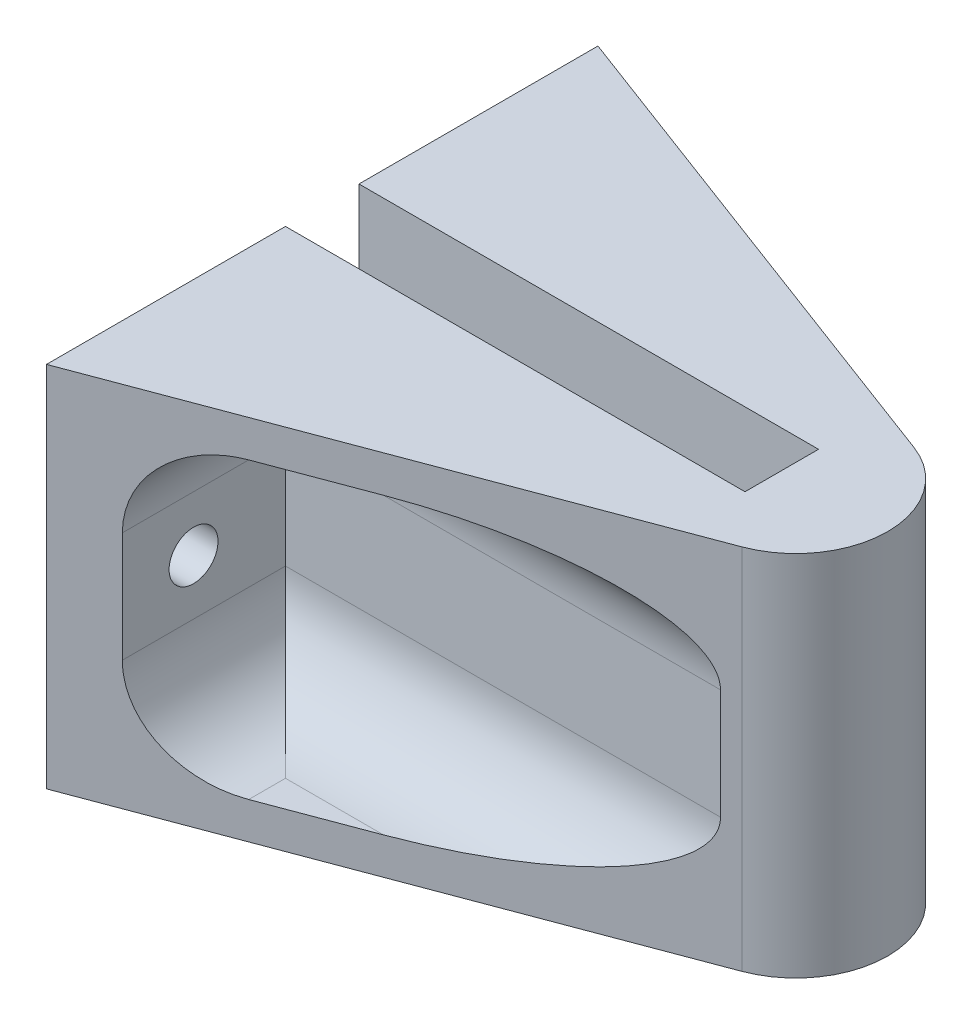
SolidWorks part; units mm, degrees
ref_plane "Спереди" through (0, 0, 0) normal (0, 0, 1) x (1, 0, 0)
ref_plane "Сверху" through (0, 0, 0) normal (0, 1, 0) x (1, 0, 0)
ref_plane "Справа" through (0, 0, 0) normal (1, 0, 0) x (0, 0, -1)
sketch "Эскиз1" plane through (0, 0, 0) normal (0, 1, 0) x (1, 0, 0)
  line L0 (0, 0) -> (0, 30)
  line L1 (0, 30) -> (40, 15)
  line L2 (40, 15) -> (0, 0)
  dimension "D1" = 30
  dimension "D2" = 40
extrude "Бобышка-Вытянуть1" add sketch "Эскиз1" along normal blind 20
sketch "Эскиз2" plane through (0, 20, 0) normal (0, 1, 0) x (1, 0, 0)
  line L0 (0, 30) -> (0, 0) construction
  line L1 (0, 13) -> (25, 13)
  line L2 (0, 13) -> (0, 17)
  line L3 (0, 17) -> (25, 17)
  line L4 (25, 13) -> (25, 17)
  point P6 (0, 21.6944)
  point P7 (0, 17.6968)
  point P8 (0, 15)
  point P9 (0, 15)
  dimension "D1" = 4
  dimension "D2" = 25
extrude "Вырез-Вытянуть1" cut sketch "Эскиз2" against normal blind 20
sketch "Эскиз3" plane through (0, 0, 0) normal (-1, 0, 0) x (0, 0, 1)
  line L0 (-30, 20) -> (-30, 0) construction
  line L1 (-30, 2) -> (-20, 2)
  line L2 (-30, 2) -> (-30, 18)
  line L3 (-30, 18) -> (-20, 18)
  line L4 (-20, 2) -> (-20, 18)
  line L5 (-15, 0) -> (-15, 21.8295) construction
  line L6 (-13, 0) -> (-17, 0) construction
  line L7 (-10, 2) -> (-10, 18)
  line L8 (0, 18) -> (-10, 18)
  line L9 (0, 2) -> (0, 18)
  line L10 (0, 2) -> (-10, 2)
  point P6 (-30, 10)
  point P7 (-30, 10)
  point P12 (-15, 21.8295)
  dimension "D1" = 16
  dimension "D2" = 10
extrude "Вырез-Вытянуть2" cut sketch "Эскиз3" against normal blind 30 from offset 3 offset against normal yes
sketch "Эскиз4" plane through (0, 0, 0) normal (-1, 0, 0) x (0, 0, 1)
  line L0 (-30, 20) -> (-30, 0) construction
  circle A0 centre (-25, 10) radius 1.3307
  circle A1 centre (-5, 10) radius 1.3307
  point P4 (0, 0)
  point P7 (-30, 10)
  point P8 (0, 0)
  point P9 (0, 0)
  dimension "D1" = 20
  dimension "D2" = 10
extrude "Вырез-Вытянуть3" cut sketch "Эскиз4" against normal blind 3
fillet "Скругление2" radius 5 1 edges at (40, 10, -15)
fillet "Скругление3" radius 5 8 edges at (3, 2, -24.4375) (14.8333, 2, -20) (3, 18, -24.4375) (14.8333, 18, -20) (14.8333, 18, -10) (3, 18, -5.5625) (3, 2, -5.5625) (14.8333, 2, -10)
